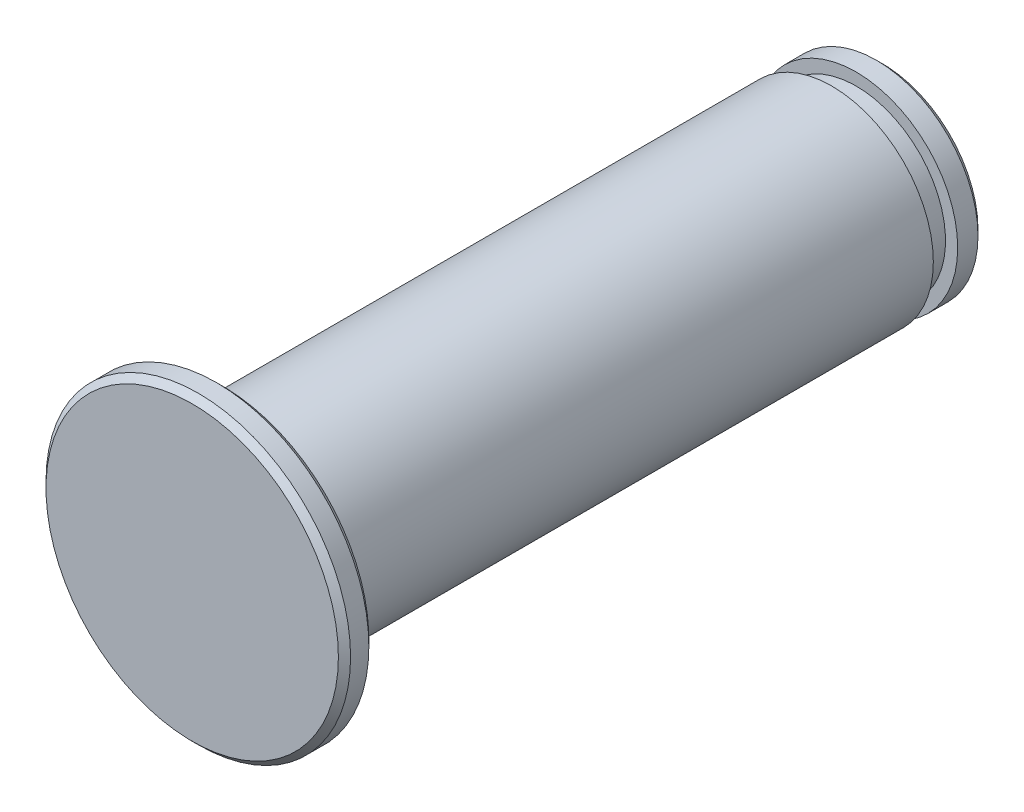
SolidWorks part; units mm, degrees
ref_plane "Front Plane" through (0, 0, 0) normal (0, 0, 1) x (1, 0, 0)
ref_plane "Top Plane" through (0, 0, 0) normal (0, 1, 0) x (1, 0, 0)
ref_plane "Right Plane" through (0, 0, 0) normal (1, 0, 0) x (0, 0, -1)
sketch "Sketch1" plane through (0, 0, 0) normal (0, 1, 0) x (1, 0, 0)
  line L0 (0, 34.4573) -> (0, -26.0378) construction
  line L1 (0, -17.6184) -> (-7.5, -17.6184)
  line L2 (-7.5, -17.6184) -> (-7.5, -16.1184)
  line L3 (-7.5, -16.1184) -> (-5, -16.1184)
  line L4 (-5, -16.1184) -> (-5, 13.8816)
  line L5 (-5, 13.8816) -> (-4.4, 13.8816)
  line L6 (-4.4, 13.8816) -> (-4.4, 15.0816)
  line L7 (-4.4, 15.0816) -> (-5, 15.0816)
  line L8 (-5, 15.0816) -> (-5, 16.3816)
  line L9 (-5, 16.3816) -> (0, 16.3816)
  line L10 (0, -17.6184) -> (0, 16.3816)
  dimension "D1" = 30
  dimension "D2" = 1.5
  dimension "D3" = 1.2
  dimension "D4" = 34
  dimension "D5" = 10
  dimension "D6" = 7.5
  dimension "D7" = 5
  dimension "D8" = 0.6
revolve "Revolve1" add sketch "Sketch1" angle 360 about L0
chamfer "Chamfer1" distance 0.3 angle 45 3 edges at (-5, 0, -16.3816) (-7.5, 0, 17.6184) (-7.5, 0, 16.1184)
